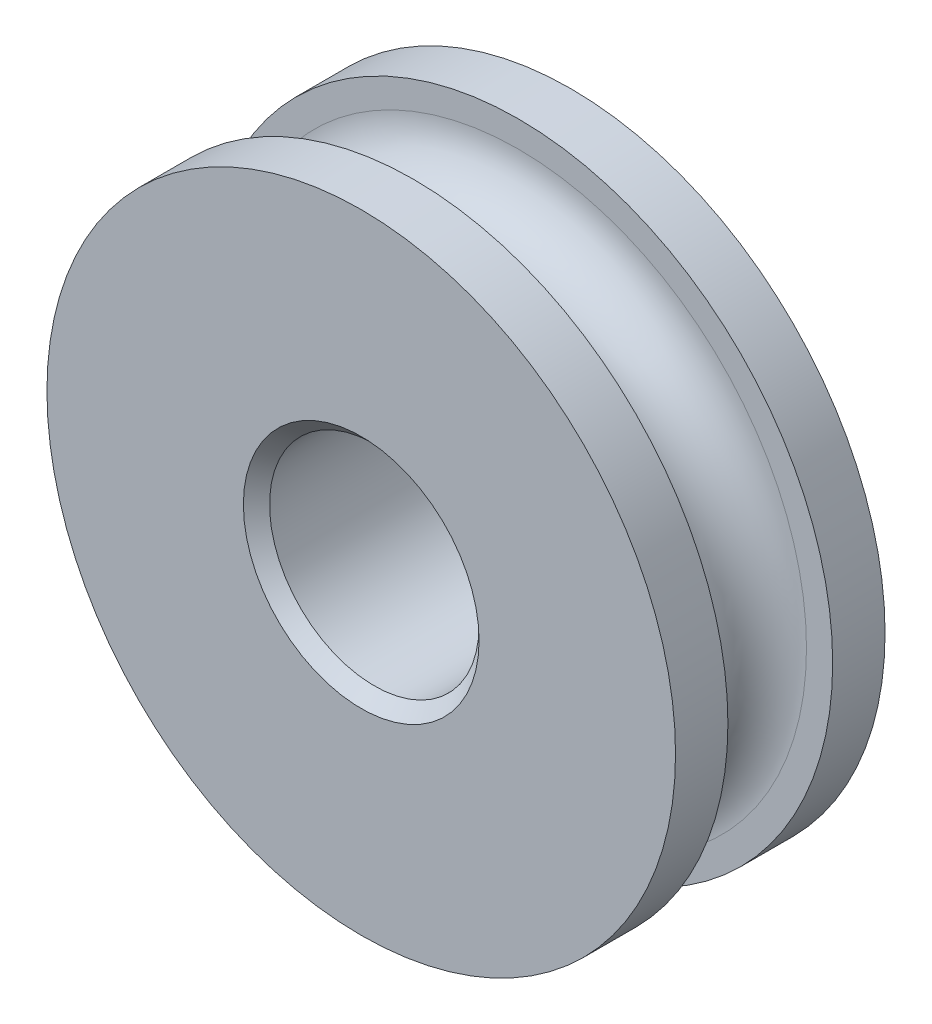
SolidWorks part; units mm, degrees
ref_plane "Front Plane" through (0, 0, 0) normal (0, 0, 1) x (1, 0, 0)
ref_plane "Top Plane" through (0, 0, 0) normal (0, 1, 0) x (1, 0, 0)
ref_plane "Right Plane" through (0, 0, 0) normal (1, 0, 0) x (0, 0, -1)
sketch "Sketch1" plane through (0, 0, 0) normal (0, 0, 1) x (1, 0, 0)
  circle A0 centre (0, 0) radius 19.05
  circle A1 centre (0, 0) radius 6.35
  dimension "D1" = 38.1
  dimension "D2" = 12.7
extrude "Extrude1" add sketch "Sketch1" along normal mid plane 12.7
sketch "Sketch2" plane through (0, 0, 0) normal (1, 0, 0) x (0, 0, -1)
  line L0 (-3.175, 17.4625) -> (-3.175, 19.05)
  line L1 (6.35, 19.05) -> (-6.35, 19.05) construction
  line L2 (3.175, 17.4625) -> (3.175, 19.05)
  line L3 (-3.175, 19.05) -> (3.175, 19.05)
  line L4 (0, 17.4625) -> (0, 0) construction
  line L5 (-6.35, 0) -> (6.35, 0) construction
  line L6 (-6.35, 19.05) -> (-6.35, -19.05) construction
  line L7 (6.35, -19.05) -> (6.35, 19.05) construction
  arc A0 (-3.175, 17.4625) -> (3.175, 17.4625) centre (0, 17.4625) ccw
  circle A1 centre (0, 17.4625) radius 3.175 construction
  dimension "D1" = 6.35
  dimension "D2" = 1.5875
chamfer "Chamfer1" distance 0.7937 angle 45 2 edges at (6.35, 0, -6.35) (6.35, 0, 6.35)
revolve "Cut-Revolve1" cut sketch "Sketch2" angle 360 about L5
